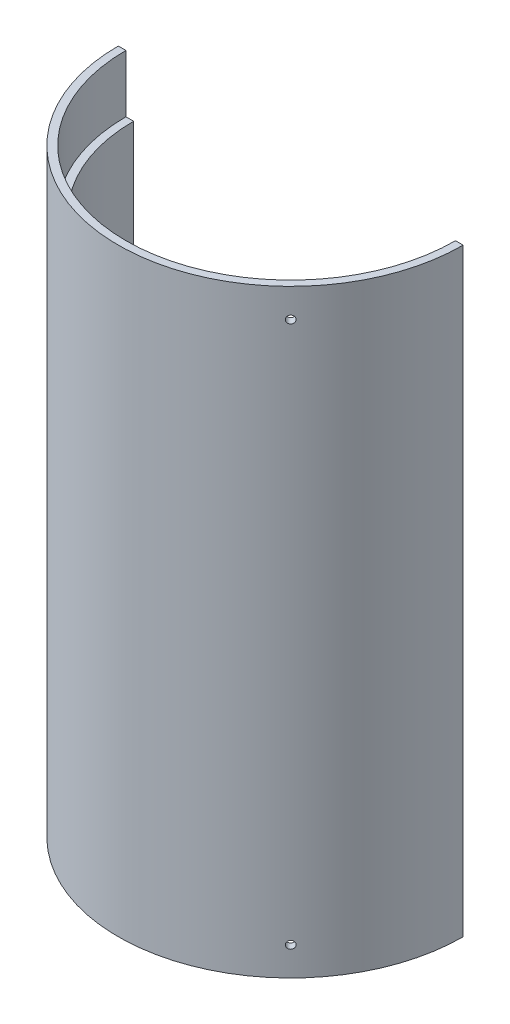
SolidWorks part; units mm, degrees
material "6061-T6 (SS)"
ref_plane "Front Plane" through (0, 0, 0) normal (0, 0, 1) x (1, 0, 0)
ref_plane "Top Plane" through (0, 0, 0) normal (0, 1, 0) x (1, 0, 0)
ref_plane "Right Plane" through (0, 0, 0) normal (1, 0, 0) x (0, 0, -1)
sketch "Sketch1" plane through (0, 0, 0) normal (0, 0, 1) x (1, 0, 0)
  line L0 (0, 0) -> (0, 68.3819) construction
  line L1 (0, 0) -> (-45, 0) construction
  line L2 (-45, 0) -> (-45, 156.3)
  line L3 (-45, 156.3) -> (-43, 156.3)
  line L4 (-43, 156.3) -> (-43, 141.3)
  line L5 (-43, 141.3) -> (-41, 141.3)
  line L6 (-41, 141.3) -> (-41, 15)
  line L7 (-41, 15) -> (-43, 15)
  line L8 (-43, 15) -> (-43, 0)
  line L9 (-43, 0) -> (-45, 0)
  dimension "D1" = 43
  dimension "D2" = 15
  dimension "D3" = 141.3
  dimension "D4" = 41
  dimension "D5" = 45
revolve "Revolve1" add sketch "Sketch1" angle 180 about L0
sketch "Sketch2" plane through (0, 0, 0) normal (1, 0, 0) x (0, 0, -1)
  line L0 (0, 0) -> (0, 6) construction
  line L1 (0, 156.3) -> (0, 0) construction
  line L2 (0, 6) -> (0, 40.3) construction
  line L3 (0, 40.3) -> (0, 91.5) construction
  circle A0 centre (0, 40.3) radius 10.45
  circle A1 centre (0, 91.5) radius 10.45
  dimension "D4" = 20.9
  dimension "D1" = 6
  dimension "D2" = 34.3
  dimension "D3" = 51.2
extrude "Cut-Extrude1" cut sketch "Sketch2" against normal through all
ref_plane "Plane1" through (0, 0, 0) normal (0.7071, 0, -0.7071) x (0, 1, 0)
sketch "Sketch3" plane through (0, 0, 0) normal (0.7071, 0, -0.7071) x (0, 1, 0)
  line L0 (0, 0) -> (7.5, 0) construction
  line L1 (0, 0) -> (68.3819, 0) construction
  line L2 (156.3, -30.4056) -> (156.3, 43) construction
  line L3 (156.3, -30.4056) -> (156.3, 43) construction
  line L4 (156.3, 0) -> (148.8, 0) construction
  circle A0 centre (7.5, 0) radius 1
  circle A1 centre (148.8, 0) radius 1
  dimension "D2" = 2
  dimension "D1" = 7.5
extrude "Cut-Extrude2" cut sketch "Sketch3" against normal through all
pattern_circular "CirPattern1" count 4 over 360 about axis through (0, 0, 0) along (0, -1, 0) of "Cut-Extrude2"
